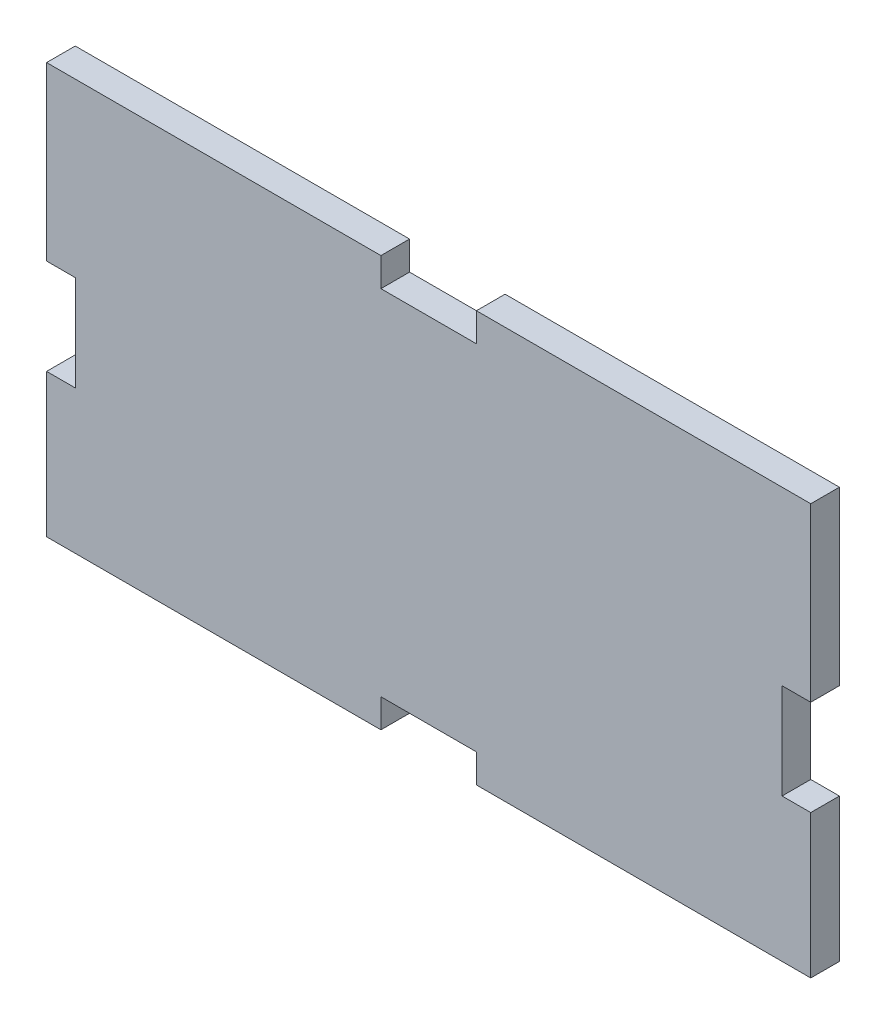
SolidWorks part; units mm, degrees
ref_plane "Front Plane" through (0, 0, 0) normal (0, 0, 1) x (1, 0, 0)
ref_plane "Top Plane" through (0, 0, 0) normal (0, 1, 0) x (1, 0, 0)
ref_plane "Right Plane" through (0, 0, 0) normal (1, 0, 0) x (0, 0, -1)
sketch "Sketch1" plane through (0, 0, 0) normal (0, 0, 1) x (1, 0, 0)
  line L0 (-32.6436, 0) -> (-32.6436, -18)
  line L1 (-32.6436, -18) -> (-29.6436, -18)
  line L2 (-29.6436, -18) -> (-29.6436, -28)
  line L3 (-29.6436, -28) -> (-32.6436, -28)
  line L4 (-32.6436, -28) -> (-32.6436, -43)
  line L5 (-32.6436, -43) -> (2.3564, -43)
  line L6 (47.3564, -43) -> (47.3564, -28)
  line L7 (47.3564, -28) -> (44.3564, -28)
  line L8 (44.3564, -28) -> (44.3564, -18)
  line L9 (44.3564, -18) -> (47.3564, -18)
  line L10 (47.3564, -18) -> (47.3564, -3)
  line L11 (-32.6436, 0) -> (2.3564, 0)
  line L12 (2.3564, 0) -> (2.3564, -3)
  line L13 (2.3564, -3) -> (12.3564, -3)
  line L16 (12.3564, -3) -> (12.3564, 0)
  line L17 (12.3564, 0) -> (47.3564, 0)
  line L18 (47.3564, 0) -> (47.3564, -3)
  line L19 (12.3564, -43) -> (47.3564, -43)
  line L21 (2.3564, -43) -> (2.3564, -40)
  line L22 (2.3564, -40) -> (12.3564, -40)
  line L23 (12.3564, -43) -> (12.3564, -40)
  point P4 (7.3564, -43)
extrude "Boss-Extrude1" add sketch "Sketch1" along normal blind 3
